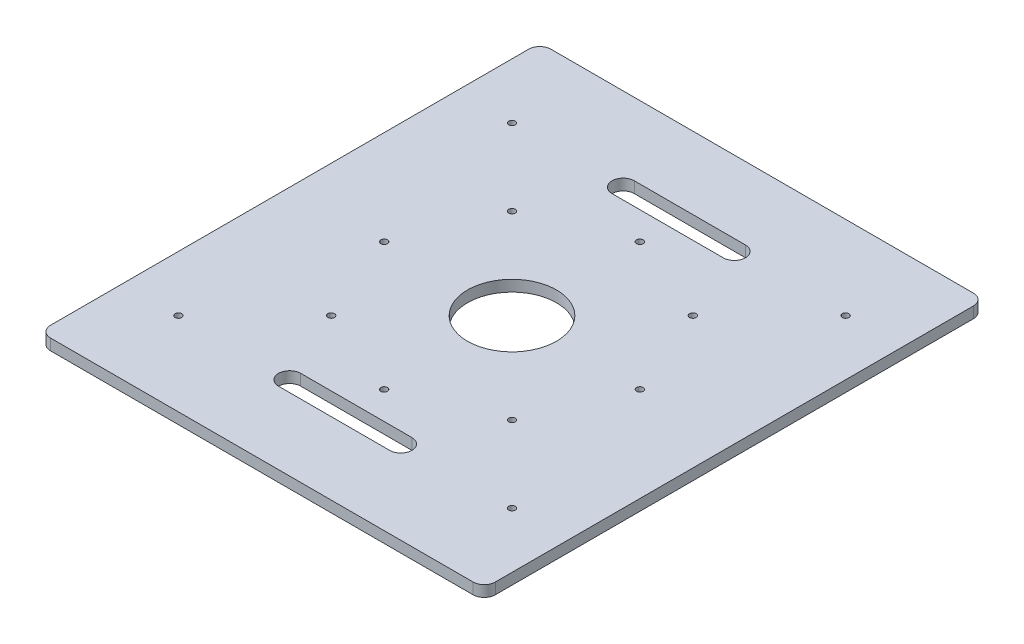
SolidWorks part; units mm, degrees
ref_plane "前基準面" through (0, 0, 0) normal (0, 0, 1) x (1, 0, 0)
ref_plane "上基準面" through (0, 0, 0) normal (0, 1, 0) x (1, 0, 0)
ref_plane "右基準面" through (0, 0, 0) normal (1, 0, 0) x (0, 0, -1)
sketch "草圖1" plane through (0, 0, 0) normal (0, 1, 0) x (1, 0, 0)
  line L0 (0, 250) -> (0, -250) construction
  line L1 (-250, 250) -> (250, 250) construction
  line L2 (-250, 250) -> (-250, -250) construction
  line L3 (-250, -250) -> (250, -250) construction
  line L4 (250, 250) -> (250, -250) construction
  line L5 (-200, 215) -> (-200, -215)
  line L6 (-200, 0) -> (200, 0) construction
  line L7 (-190, 225) -> (190, 225)
  line L9 (-190, -225) -> (190, -225)
  line L11 (0, -225) -> (0, 225) construction
  line L12 (-200, 0) -> (200, 0) construction
  line L31 (200, 215) -> (200, -215)
  arc A0 (200, 215) -> (190, 225) centre (190, 215) ccw
  arc A1 (-190, 225) -> (-200, 215) centre (-190, 215) ccw
  arc A2 (190, -225) -> (200, -215) centre (190, -215) ccw
  arc A3 (-200, -215) -> (-190, -225) centre (-190, -215) ccw
  point P0 (0, 0)
  point P8 (0, 0)
  point P11 (0, 0)
  point P38 (200, 225)
  point P41 (-200, 225)
  point P44 (200, -225)
  dimension "D9" = 10
  dimension "D1" = 500
  dimension "D2" = 500
  dimension "D3" = 400
  dimension "D4" = 450
extrude "填料-伸長1" add sketch "草圖1" along normal blind 10
sketch "草圖3" plane through (0, 10, 0) normal (0, 1, 0) x (1, 0, 0)
  line L0 (0, 240.0553) -> (0, -270.0297) construction
  line L1 (-314.6258, 0) -> (222.5458, 0) construction
  line L8 (-150, 150) -> (150, 150) construction
  line L9 (165, -165) -> (135, -165) construction
  line L12 (-150, 150) -> (-150, -150) construction
  line L13 (-165, -135) -> (-135, -135) construction
  line L22 (-150, -150) -> (150, -150) construction
  line L23 (150, 150) -> (150, -150) construction
  line L24 (-165, -135) -> (-165, -165) construction
  line L25 (-165, -165) -> (-135, -165) construction
  line L26 (-135, -135) -> (-135, -165) construction
  line L27 (-150, -165) -> (-150, -135) construction
  line L28 (-165, -150) -> (-135, -150) construction
  line L29 (135, -135) -> (135, -165) construction
  line L30 (165, -135) -> (135, -135) construction
  line L31 (165, -135) -> (165, -165) construction
  line L32 (-165, 165) -> (-135, 165) construction
  line L33 (-135, 135) -> (-135, 165) construction
  line L34 (-165, 135) -> (-135, 135) construction
  line L35 (-165, 135) -> (-165, 165) construction
  line L36 (165, 135) -> (165, 165) construction
  line L37 (165, 135) -> (135, 135) construction
  line L38 (135, 135) -> (135, 165) construction
  line L39 (165, 165) -> (135, 165) construction
  line L40 (-50, -150) -> (50, -150) construction
  line L41 (-50, -140) -> (50, -140)
  line L42 (-50, -160) -> (50, -160)
  line L43 (-50, 150) -> (50, 150) construction
  line L44 (-50, 140) -> (50, 140)
  line L45 (-50, 160) -> (50, 160)
  circle A0 centre (0, 0) radius 60 construction
  circle A1 centre (0, 0) radius 40
  circle A2 centre (0, 115) radius 3
  circle A3 centre (81.3173, 81.3173) radius 3
  circle A4 centre (115, 0) radius 3
  circle A5 centre (81.3173, -81.3173) radius 3
  circle A6 centre (0, -115) radius 3
  circle A7 centre (-81.3173, -81.3173) radius 3
  circle A8 centre (-115, 0) radius 3
  circle A9 centre (-81.3173, 81.3173) radius 3
  circle A10 centre (-150, 150) radius 3
  circle A12 centre (150, 150) radius 3
  circle A13 centre (-150, -150) radius 3
  circle A14 centre (150, -150) radius 3
  arc A15 (-50, -140) -> (-50, -160) centre (-50, -150) ccw
  arc A16 (50, -160) -> (50, -140) centre (50, -150) ccw
  arc A17 (-50, 140) -> (-50, 160) centre (-50, 150) cw
  arc A18 (50, 160) -> (50, 140) centre (50, 150) cw
  point P5 (150, 0)
  point P28 (0, 0)
  point P31 (0, -150)
  point P56 (0, -150)
  point P65 (0, 150)
  dimension "D1" = 120
  dimension "D3" = 6
  dimension "D4" = 115
  dimension "D11" = 10
  dimension "D10" = 6
  dimension "D6" = 300
  dimension "D7" = 300
  dimension "D8" = 30
  dimension "D9" = 30
  dimension "D12" = 100
  dimension "D2" = 20
  dimension "D5" = 8
extrude "除料-伸長1" cut sketch "草圖3" against normal blind 15
